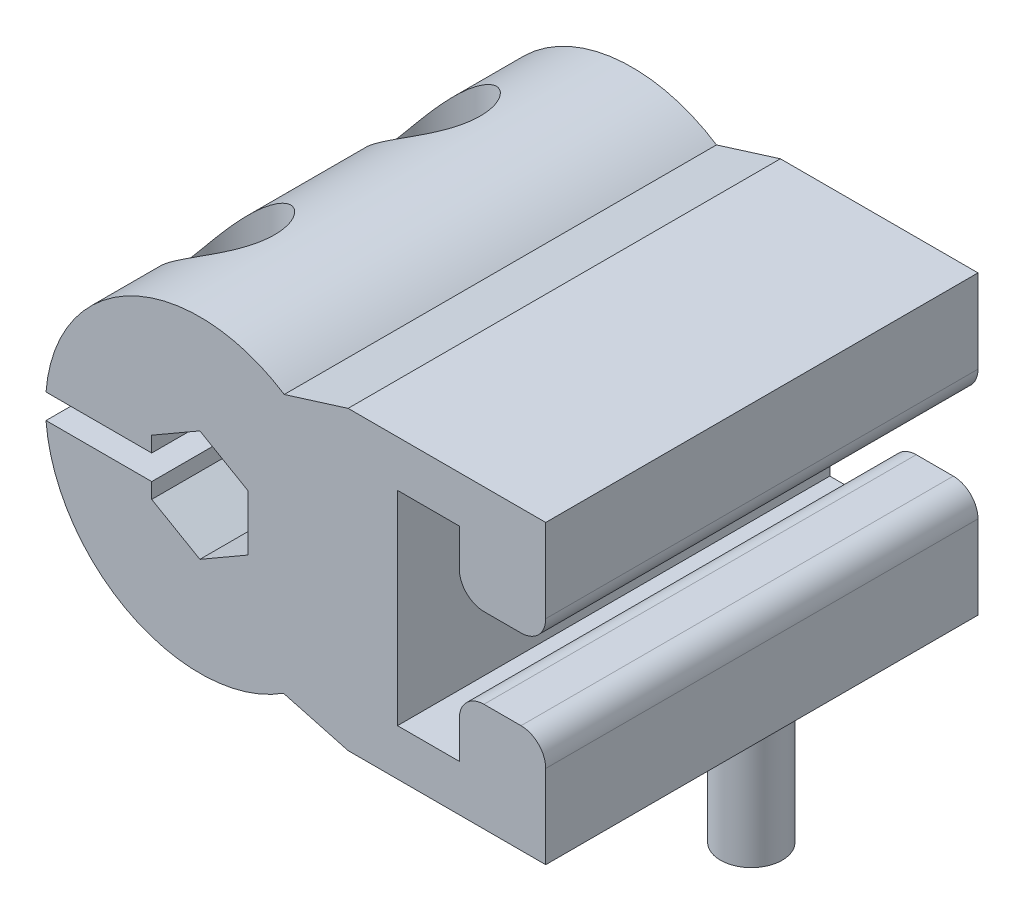
SolidWorks part; units mm, degrees
ref_plane "Front Plane" through (0, 0, 0) normal (0, 0, 1) x (1, 0, 0)
ref_plane "Top Plane" through (0, 0, 0) normal (0, 1, 0) x (1, 0, 0)
ref_plane "Right Plane" through (0, 0, 0) normal (1, 0, 0) x (0, 0, -1)
sketch "Sketch1" plane through (0, 0, 0) normal (0, 0, 1) x (1, 0, 0)
  line L0 (-20.2969, 1) -> (-3.9, 1)
  line L1 (-3.9, 2.2517) -> (-3.9, 1)
  line L2 (-3.9, -2.2517) -> (0, -4.5033)
  line L3 (0, -4.5033) -> (3.9, -2.2517)
  line L4 (3.9, -2.2517) -> (3.9, 2.2517)
  line L5 (3.9, 2.2517) -> (0, 4.5033)
  line L6 (0, 4.5033) -> (-3.9, 2.2517)
  line L7 (-3.9, 0) -> (-22.8855, 0) construction
  line L8 (-20.2969, -1) -> (-3.9, -1)
  line L9 (-20.2969, 1) -> (-20.2969, -1)
  line L10 (-3.9, -1) -> (-3.9, -2.2517)
  arc A0 (-1.95, -3.3775) -> (-1.95, 3.3775) centre (0, 0) ccw construction
  circle A1 centre (0, 0) radius 12.5
  dimension "D2" = 25
  dimension "D1" = 7.8
  dimension "D3" = 1
extrude "Boss-Extrude1" add sketch "Sketch1" along normal blind 35 contours L8 A1 L0 L1 L6 L5 L4 L3 L2 L10
ref_plane "Plane1" through (0, 12.5, 0) normal (0, 1, 0) x (1, 0, 0)
sketch "Sketch2" plane through (0, 12.5, 0) normal (0, 1, 0) x (1, 0, 0)
  line L0 (-12.4599, 0) -> (-7.0788, -9.1755) construction
  line L1 (-7.0788, -9.1755) -> (-7.0788, -25.8245) construction
  line L2 (-7.0788, -25.8245) -> (-12.4599, -35) construction
  circle A0 centre (-7.0788, -9.1755) radius 1.8669
  circle A1 centre (-7.0788, -25.8245) radius 1.8669
  dimension "D1" = 3.7338
extrude "Cut-Extrude1" cut sketch "Sketch2" against normal through all
sketch "Sketch3" plane through (0, 12.5, 0) normal (0, 1, 0) x (1, 0, 0)
  circle A0 centre (-7.0788, -9.1755) radius 3.9497
  circle A1 centre (-7.0788, -25.8245) radius 3.9497
  dimension "D1" = 7.8994
extrude "Cut-Extrude2" cut sketch "Sketch3" against normal blind 8
ref_plane "Plane2" through (0, -12.5, 0) normal (0, -1, 0) x (-1, 0, 0)
sketch "Sketch4" plane through (0, -12.5, 0) normal (0, -1, 0) x (-1, 0, 0)
  line L1 (7.0788, -5.2307) -> (3.6625, -7.2031)
  line L2 (3.6625, -7.2031) -> (3.6625, -11.1479)
  line L3 (3.6625, -11.1479) -> (7.0788, -13.1203)
  line L4 (7.0788, -13.1203) -> (10.4951, -11.1479)
  line L5 (10.4951, -11.1479) -> (10.4951, -7.2031)
  line L6 (10.4951, -7.2031) -> (7.0788, -5.2307)
  line L7 (7.0788, -21.8797) -> (3.6625, -23.8521)
  line L8 (3.6625, -23.8521) -> (3.6625, -27.7969)
  line L9 (3.6625, -27.7969) -> (7.0788, -29.7693)
  line L10 (7.0788, -29.7693) -> (10.4951, -27.7969)
  line L11 (10.4951, -27.7969) -> (10.4951, -23.8521)
  line L12 (10.4951, -23.8521) -> (7.0788, -21.8797)
  circle A0 centre (7.0788, -9.1755) radius 3.4163 construction
  circle A1 centre (7.0788, -25.8245) radius 3.4163 construction
  dimension "D1" = 6.8326
extrude "Cut-Extrude3" cut sketch "Sketch4" against normal blind 8
sketch "Sketch5" plane through (0, 0, 0) normal (0, 0, -1) x (-1, 0, 0)
  line L0 (-12, 12.0833) -> (-6.8279, 10.4704)
  line L5 (-12, -11.9167) -> (-6.7683, -10.509)
  line L6 (-21, 3.3333) -> (-21, 8.3333)
  line L19 (-12, -11.9167) -> (-28, -11.9167)
  line L21 (-12, 12.0833) -> (-28, 12.0833)
  line L22 (-28, -11.9167) -> (-28, -3.1667)
  line L23 (-16, -8.1667) -> (-21, -8.1667)
  line L24 (-16, -8.1667) -> (-16, 8.3333)
  line L25 (-16, 8.3333) -> (-21, 8.3333)
  line L26 (-21, -8.1667) -> (-21, -3.1667)
  line L27 (-21, -3.1667) -> (-28, -3.1667)
  line L29 (-21, 3.3333) -> (-28, 3.3333)
  line L31 (-28, 3.3333) -> (-28, 12.0833)
  line L34 (0, 12.5) -> (0, -12.5) construction
  arc A0 (12.4599, 1) -> (12.4599, -1) centre (0, 0) ccw construction
  arc A1 (-6.8279, 10.4704) -> (-6.7683, -10.509) centre (0, 0) ccw
  dimension "D5" = 7
  dimension "D1" = 16.5
  dimension "D2" = 24
  dimension "D3" = 6.5
  dimension "D6" = 12
  dimension "D7" = 28
extrude "Boss-Extrude2" add sketch "Sketch5" against normal through all
fillet "Fillet1" radius 2 4 edges at (21, -3.1667, 17.5) (21, 3.3333, 17.5) (28, 3.3333, 17.5) (28, -3.1667, 17.5)
sketch "Sketch6" plane through (0, -11.9167, 0) normal (0, -1, 0) x (1, 0, 0)
  circle A0 centre (21.7627, 12.1144) radius 2.5
  dimension "D1" = 5
extrude "Boss-Extrude3" add sketch "Sketch6" along normal blind 13
fillet "Fillet2" radius 2 1 edges at (21.7627, -11.9167, 9.6144)
